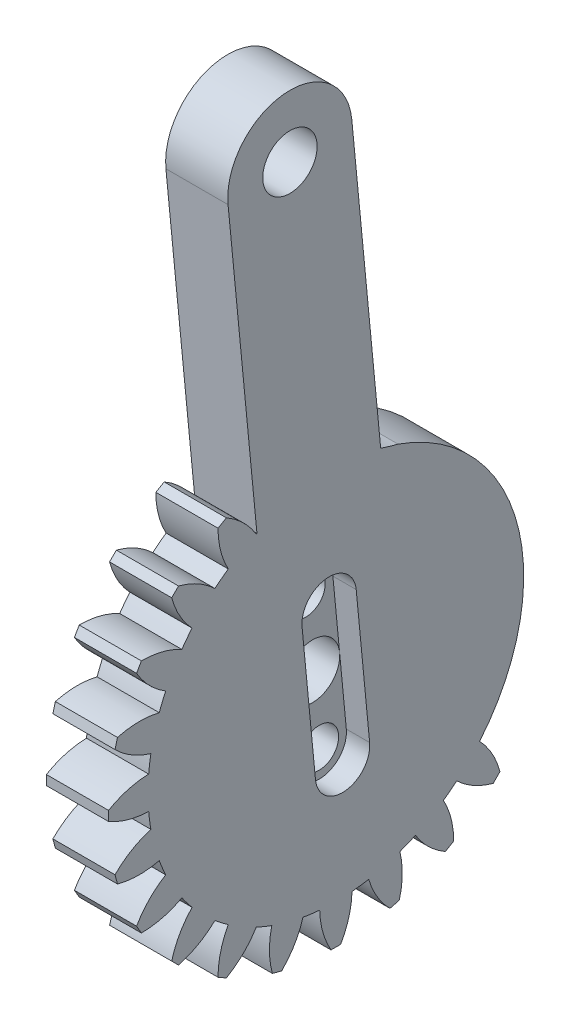
SolidWorks part; units mm, degrees
ref_plane "Front Plane" through (0, 0, 0) normal (1, 0, 0) x (0, 1, 0)
ref_plane "Top Plane" through (0, 0, 0) normal (0, 0, 1) x (0, 1, 0)
ref_plane "Right Plane" through (0, 0, 0) normal (0, 1, 0) x (-1, 0, 0)
sketch "Sketch1" plane through (0, 0, 0) normal (1, 0, 0) x (0, 1, 0)
  line L0 (0, 0) -> (30.75, 0) construction
  line L1 (0, 14.63) -> (0, -14.63) construction
  line L2 (-0.31, 14.63) -> (0.31, 14.63)
  line L3 (3.4871, 14.2117) -> (4.086, 14.0513)
  line L4 (7.0465, 12.825) -> (7.5835, 12.515)
  line L5 (10.1258, 10.5642) -> (10.5642, 10.1258)
  line L6 (12.515, 7.5835) -> (12.825, 7.0465)
  line L7 (35.4703, 3.4245) -> (0, 0) construction
  line L8 (30.2233, 6.9365) -> (10.9719, 5.0779)
  line L9 (30.9921, -1.0265) -> (11.7407, -2.8851)
  line L10 (12.825, -7.0465) -> (12.515, -7.5835)
  line L11 (10.5642, -10.1258) -> (10.1258, -10.5642)
  line L12 (7.5835, -12.515) -> (7.0465, -12.825)
  line L13 (4.086, -14.0513) -> (3.4871, -14.2117)
  line L14 (0.31, -14.63) -> (-0.31, -14.63)
  line L15 (-3.4871, -14.2117) -> (-4.086, -14.0513)
  line L16 (-7.0465, -12.825) -> (-7.5835, -12.515)
  line L17 (-10.1258, -10.5642) -> (-10.5642, -10.1258)
  line L18 (-12.515, -7.5835) -> (-12.825, -7.0465)
  line L19 (-14.0513, -4.086) -> (-14.2117, -3.4871)
  line L20 (-14.63, -0.31) -> (-14.63, 0.31)
  line L21 (-14.2117, 3.4871) -> (-14.0513, 4.086)
  line L22 (-12.825, 7.0465) -> (-12.515, 7.5835)
  line L23 (-10.5642, 10.1258) -> (-10.1258, 10.5642)
  line L24 (-7.5835, 12.515) -> (-7.0465, 12.825)
  line L25 (-4.086, 14.0513) -> (-3.4871, 14.2117)
  line L26 (30.75, 4) -> (30.75, -4) construction
  line L27 (30.75, 4) -> (11.4091, 4) construction
  line L28 (30.75, -4) -> (11.4091, -4) construction
  line L29 (14.0743, 4) -> (14.2117, 3.4871) [skipped]
  line L30 (14.63, 0) -> (14.63, -0.31) [skipped]
  line L31 (14.0743, -4) -> (14.0513, -4.086) [skipped]
  arc A0 (-6.9233, 9.9114) -> (-7.7818, 9.2526) centre (0, 0) ccw
  circle A1 centre (0, 0) radius 1.75
  circle A2 centre (30.75, 0) radius 1.75 construction
  arc A3 (-1.04, 12.0452) -> (-0.31, 14.63) centre (4.3585, 11.9161) cw
  arc A4 (1.04, 12.0452) -> (0.31, 14.63) centre (-4.3585, 11.9161) ccw
  arc A5 (2.113, 11.9039) -> (3.4871, 14.2117) centre (7.294, 10.382) cw
  arc A6 (4.1221, 11.3656) -> (4.086, 14.0513) centre (-1.1258, 12.6381) ccw
  arc A7 (5.1219, 10.9514) -> (7.0465, 12.825) centre (9.7326, 8.1404) cw
  arc A8 (6.9233, 9.9114) -> (7.5835, 12.515) centre (2.1835, 12.4988) ccw
  arc A9 (7.7818, 9.2526) -> (10.1258, 10.5642) centre (11.5078, 5.344) cw
  arc A10 (9.2526, 7.7818) -> (10.5642, 10.1258) centre (5.344, 11.5078) ccw
  arc A11 (9.9114, 6.9233) -> (12.515, 7.5835) centre (12.4988, 2.1835) cw
  arc A12 (10.9514, 5.1219) -> (12.825, 7.0465) centre (8.1404, 9.7326) ccw
  arc A13 (10.9719, 5.0779) -> (10.9514, 5.1219) centre (0, 0) ccw
  arc A15 (-9.2526, 7.7818) -> (-9.9114, 6.9233) centre (0, 0) ccw
  arc A16 (-6.9233, 9.9114) -> (-7.7818, 9.2526) centre (0, 0) ccw
  arc A17 (-4.1221, 11.3656) -> (-5.1219, 10.9514) centre (0, 0) ccw
  arc A18 (2.113, 11.9039) -> (1.04, 12.0452) centre (0, 0) ccw
  arc A19 (10.9514, -5.1219) -> (12.825, -7.0465) centre (8.1404, -9.7326) cw
  arc A20 (9.9114, -6.9233) -> (12.515, -7.5835) centre (12.4988, -2.1835) ccw
  arc A21 (9.2526, -7.7818) -> (10.5642, -10.1258) centre (5.344, -11.5078) cw
  arc A22 (7.7818, -9.2526) -> (10.1258, -10.5642) centre (11.5078, -5.344) ccw
  arc A23 (6.9233, -9.9114) -> (7.5835, -12.515) centre (2.1835, -12.4988) cw
  arc A24 (5.1219, -10.9514) -> (7.0465, -12.825) centre (9.7326, -8.1404) ccw
  arc A25 (4.1221, -11.3656) -> (4.086, -14.0513) centre (-1.1258, -12.6381) cw
  arc A26 (2.113, -11.9039) -> (3.4871, -14.2117) centre (7.294, -10.382) ccw
  arc A27 (1.04, -12.0452) -> (0.31, -14.63) centre (-4.3585, -11.9161) cw
  arc A28 (-1.04, -12.0452) -> (-0.31, -14.63) centre (4.3585, -11.9161) ccw
  arc A29 (-2.113, -11.9039) -> (-3.4871, -14.2117) centre (-7.294, -10.382) cw
  arc A30 (-4.1221, -11.3656) -> (-4.086, -14.0513) centre (1.1258, -12.6381) ccw
  arc A31 (-5.1219, -10.9514) -> (-7.0465, -12.825) centre (-9.7326, -8.1404) cw
  arc A32 (-6.9233, -9.9114) -> (-7.5835, -12.515) centre (-2.1835, -12.4988) ccw
  arc A33 (-7.7818, -9.2526) -> (-10.1258, -10.5642) centre (-11.5078, -5.344) cw
  arc A34 (-9.2526, -7.7818) -> (-10.5642, -10.1258) centre (-5.344, -11.5078) ccw
  arc A35 (-9.9114, -6.9233) -> (-12.515, -7.5835) centre (-12.4988, -2.1835) cw
  arc A36 (-10.9514, -5.1219) -> (-12.825, -7.0465) centre (-8.1404, -9.7326) ccw
  arc A37 (-11.3656, -4.1221) -> (-14.0513, -4.086) centre (-12.6381, 1.1258) cw
  arc A38 (-11.9039, -2.113) -> (-14.2117, -3.4871) centre (-10.382, -7.294) ccw
  arc A39 (-12.0452, -1.04) -> (-14.63, -0.31) centre (-11.9161, 4.3585) cw
  arc A40 (-12.0452, 1.04) -> (-14.63, 0.31) centre (-11.9161, -4.3585) ccw
  arc A41 (-11.9039, 2.113) -> (-14.2117, 3.4871) centre (-10.382, 7.294) cw
  arc A42 (-11.3656, 4.1221) -> (-14.0513, 4.086) centre (-12.6381, -1.1258) ccw
  arc A43 (-10.9514, 5.1219) -> (-12.825, 7.0465) centre (-8.1404, 9.7326) cw
  arc A44 (-9.9114, 6.9233) -> (-12.515, 7.5835) centre (-12.4988, 2.1835) ccw
  arc A45 (-9.2526, 7.7818) -> (-10.5642, 10.1258) centre (-5.344, 11.5078) cw
  arc A46 (-7.7818, 9.2526) -> (-10.1258, 10.5642) centre (-11.5078, 5.344) ccw
  arc A47 (-6.9233, 9.9114) -> (-7.5835, 12.515) centre (-2.1835, 12.4988) cw
  arc A48 (-5.1219, 10.9514) -> (-7.0465, 12.825) centre (-9.7326, 8.1404) ccw
  arc A49 (-4.1221, 11.3656) -> (-4.086, 14.0513) centre (1.1258, 12.6381) cw
  arc A50 (-2.113, 11.9039) -> (-3.4871, 14.2117) centre (-7.294, 10.382) ccw
  arc A51 (30.75, -4) -> (30.75, 4) centre (30.75, 0) ccw construction
  arc A52 (-4.1221, 11.3656) -> (-5.1219, 10.9514) centre (0, 0) ccw
  arc A53 (-9.2526, 7.7818) -> (-9.9114, 6.9233) centre (0, 0) ccw
  arc A54 (-10.9514, 5.1219) -> (-11.3656, 4.1221) centre (0, 0) ccw
  arc A55 (-11.9039, 2.113) -> (-12.0452, 1.04) centre (0, 0) ccw
  arc A56 (-12.0452, -1.04) -> (-11.9039, -2.113) centre (0, 0) ccw
  arc A57 (-11.3656, -4.1221) -> (-10.9514, -5.1219) centre (0, 0) ccw
  arc A58 (-9.9114, -6.9233) -> (11.4091, -4) centre (0, 0) ccw
  arc A59 (-1.04, 12.0452) -> (-2.113, 11.9039) centre (0, 0) ccw
  arc A60 (2.113, 11.9039) -> (1.04, 12.0452) centre (0, 0) ccw
  arc A61 (5.1219, 10.9514) -> (4.1221, 11.3656) centre (0, 0) ccw
  arc A62 (7.7818, 9.2526) -> (6.9233, 9.9114) centre (0, 0) ccw
  arc A63 (9.9114, 6.9233) -> (9.2526, 7.7818) centre (0, 0) ccw
  arc A64 (11.3656, 4.1221) -> (14.0513, 4.086) centre (12.6381, -1.1258) cw [skipped]
  arc A65 (11.9039, 2.113) -> (14.2117, 3.4871) centre (10.382, 7.294) ccw [skipped]
  arc A66 (12.0452, 1.04) -> (14.63, 0.31) centre (11.9161, -4.3585) cw [skipped]
  arc A67 (12.0452, -1.04) -> (14.63, -0.31) centre (11.9161, 4.3585) ccw [skipped]
  arc A68 (11.9039, -2.113) -> (14.2117, -3.4871) centre (10.382, -7.294) cw [skipped]
  arc A69 (11.3656, -4.1221) -> (14.0513, -4.086) centre (12.6381, 1.1258) ccw [skipped]
  arc A70 (5.1219, 10.9514) -> (4.1221, 11.3656) centre (0, 0) ccw
  arc A71 (7.7818, 9.2526) -> (6.9233, 9.9114) centre (0, 0) ccw
  arc A72 (9.9114, 6.9233) -> (9.2526, 7.7818) centre (0, 0) ccw
  arc A73 (-1.04, 12.0452) -> (-2.113, 11.9039) centre (0, 0) ccw
  arc A74 (-10.9514, 5.1219) -> (-11.3656, 4.1221) centre (0, 0) ccw
  arc A75 (-11.9039, 2.113) -> (-12.0452, 1.04) centre (0, 0) ccw
  arc A76 (-12.0452, -1.04) -> (11.4091, -4) centre (0, 0) ccw
  arc A77 (10.9719, 5.0779) -> (10.9514, 5.1219) centre (0, 0) ccw
  circle A78 centre (30.6077, 2.955) radius 4
  arc A79 (11.7407, -2.8851) -> (11.4091, -4) centre (23.1498, -6.8851) ccw
  circle A80 centre (30.6077, 2.955) radius 1.75
  point P8 (0, 0)
  point P46 (10.9617, 5.0999)
  dimension "D2" = 24.18
  dimension "D3" = 3.5
  dimension "D4" = 3.5
  dimension "D6" = 5.4
  dimension "D10" = 8
  dimension "D11" = 30.75
  dimension "D12" = 5.515
  dimension "D13" = 8
  dimension "D14" = 12.09
  dimension "D15" = 3.5
  dimension "D1" = 30.75
  dimension "D5" = 29.26
  dimension "D7" = 1.04
  dimension "D8" = 0.31
  dimension "D9" = 24
extrude "Boss-Extrude1" add sketch "Sketch1" along normal blind 4 contours A11 A63 A10 L5 A9 A62 A8 L4 A7 A61 A6 L3 A5 A60 A4 L2 A3 A59 A50 L25 A49 A52 A48 L24 A47 A0 A46 L23 A45 A53 A44 L22 A43 A54 A42 L21 A41 A55 A40 L20 A39 A56 A38 L19 A37 A57 A36 L18 A35 A58 | A78 A80 | A76 A38 L19 A37 | A76 A36 L18 A35 | A58 A34 L17 A33
sketch "Sketch2" plane through (0, 0, 0) normal (-1, 0, 0) x (0, -1, 0)
  circle A0 centre (0, 0) radius 13 construction
  dimension "D1" = 26
sketch "Sketch3" plane through (0, 0, 0) normal (-1, 0, 0) x (0, -1, 0)
  line L0 (0, 0) -> (-30.6077, 2.955) construction
  line L1 (0, 0) -> (-0.4859, -5.0332) construction
  circle A0 centre (-30.6077, 2.955) radius 1.75 construction
  circle A1 centre (-4.4792, 0.4324) radius 1.25
  circle A2 centre (4.4792, -0.4324) radius 1.25
  dimension "D2" = 2.5
  dimension "D1" = 4.5
extrude "Cut-Extrude1" cut sketch "Sketch3" against normal through all
sketch "Sketch4" plane through (0, 0, 0) normal (-1, 0, 0) x (0, -1, 0)
  line L0 (4.6473, 1.3095) -> (-4.311, 2.1743)
  line L1 (4.6473, 1.3095) -> (4.311, -2.1743)
  line L2 (-4.311, 2.1743) -> (-4.6473, -1.3095)
  line L3 (4.311, -2.1743) -> (-4.6473, -1.3095)
  line L4 (0, 0) -> (-0.4859, -5.0332) construction
  circle A0 centre (0, 0) radius 1.75 construction
  circle A2 centre (4.4792, -0.4324) radius 1.75
  circle A3 centre (-4.4792, 0.4324) radius 1.75
extrude "Cut-Extrude2" cut sketch "Sketch4" along normal blind 1.5 from surface at -4 contours L1 A2 | L1 A2 | L2 A3 | L2 A3 | A3 L3 A2 L0 starting at face at (4, 4.4792, 1.6824)
